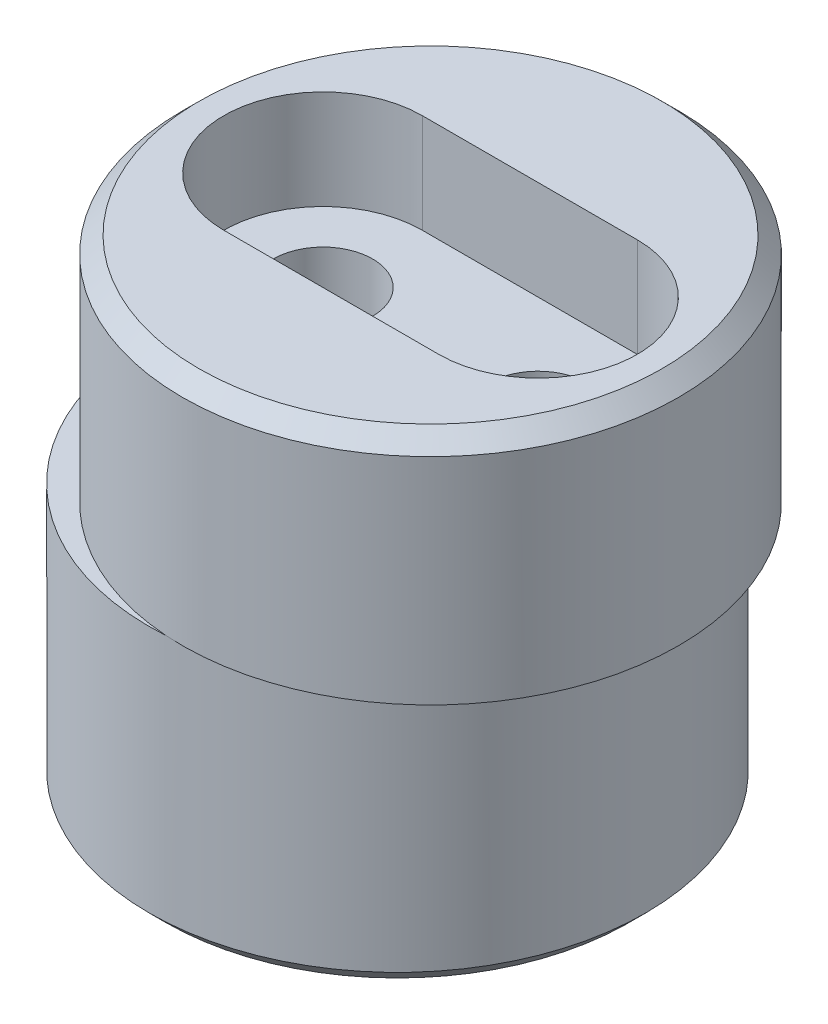
SolidWorks part; units mm, degrees
material "Cast Stainless Steel"
ref_plane "Front Plane" through (0, 0, 0) normal (0, 0, 1) x (1, 0, 0)
ref_plane "Top Plane" through (0, 0, 0) normal (0, 1, 0) x (1, 0, 0)
ref_plane "Right Plane" through (0, 0, 0) normal (1, 0, 0) x (0, 0, -1)
sketch "Sketch1" plane through (0, 0, 0) normal (0, 1, 0) x (1, 0, 0)
  circle A0 centre (0, 0) radius 7.5
  dimension "Outer Diameter" = 15
extrude "Boss-Extrude1" add sketch "Sketch1" along normal blind 8
sketch "Sketch2" plane through (0, 8, 0) normal (0, 1, 0) x (1, 0, 0)
  line L0 (0, 0) -> (1, 0) construction
  circle A0 centre (1, 0) radius 7.5
  dimension "First Cycloid Base" = 15
  dimension "Eccentricity" = 1
extrude "Boss-Extrude2" add sketch "Sketch2" along normal blind 7
sketch "Sketch3" plane through (0, 15, 0) normal (0, 1, 0) x (1, 0, 0)
  line L0 (-2.25, 0) -> (4.25, 0) construction
  circle A0 centre (-2.25, 0) radius 1.5
  circle A1 centre (1, 0) radius 7.5
  circle A2 centre (1, 0) radius 7.5 construction
  circle A3 centre (4.25, 0) radius 1.5
  point P7 (1, 0)
  dimension "D3" = 3
  dimension "D2" = 6.5
  dimension "D1" = 0
extrude "Cut-Extrude1" cut sketch "Sketch3" against normal through all
sketch "Sketch5" plane through (0, 15, 0) normal (0, 1, 0) x (1, 0, 0)
  line L0 (4.25, 0) -> (-2.25, 0) construction
  line L1 (-2.25, 0) -> (4.25, 0) construction
  line L2 (-2.25, 3) -> (4.25, 3)
  line L3 (-2.25, -3) -> (4.25, -3)
  circle A0 centre (1, 0) radius 7.5 construction
  arc A3 (-2.25, 3) -> (-2.25, -3) centre (-2.25, 0) ccw
  arc A4 (4.25, -3) -> (4.25, 3) centre (4.25, 0) ccw
  point P0 (1, 0)
  point P5 (1, 0)
  dimension "D2" = 3
  dimension "D1" = 6.5
extrude "Cut-Extrude3" cut sketch "Sketch5" against normal blind 3
chamfer "Chamfer1" distance 0.5 angle 45 2 edges at (0, 0, 7.5) (1, 15, 7.5)
equation "\"Outer Diameter\"= 15"
equation "\"Outer Diameter@Sketch1\"=\"Outer Diameter\""
equation "\"Bottom Thickness\"= 8"
equation "\"D1@Boss-Extrude1\"=\"Bottom Thickness\""
equation "\"Bottom Cycloid Diameter\"= 15"
equation "\"First Cycloid Base@Sketch2\"=\"Bottom Cycloid Diameter\""
equation "\"Bottom Cycloid Thickness\"= 7"
equation "\"D1@Boss-Extrude2\"=\"Bottom Cycloid Thickness\""
equation "\"Eccentricity\"= 1"
equation "\"Top Cycloid Diameter\"= 10"
equation "\"Top Base Diameter\"= 10"
equation "\"Top Base Thickness\"= 5"
equation "\"E\"= 1"
equation "\"Eccentricity@Sketch2\"=\"E\""
